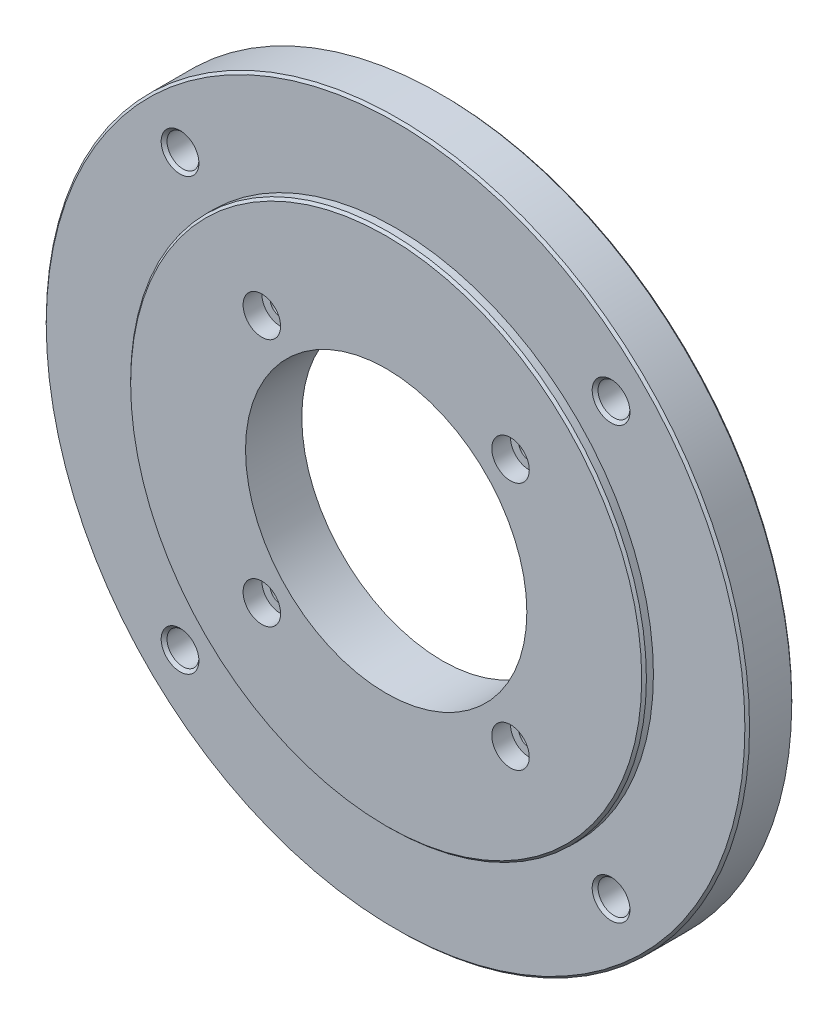
SolidWorks part; units mm, degrees
ref_plane "Front Plane" through (0, 0, 0) normal (0, 0, 1) x (1, 0, 0)
ref_plane "Top Plane" through (0, 0, 0) normal (0, 1, 0) x (1, 0, 0)
ref_plane "Right Plane" through (0, 0, 0) normal (1, 0, 0) x (0, 0, -1)
sketch "Sketch1" plane through (0, 0, 0) normal (0, 0, 1) x (1, 0, 0)
  circle A0 centre (0, 0) radius 75
  dimension "D1" = 150
extrude "Boss-Extrude1" add sketch "Sketch1" along normal blind 10
sketch "Sketch2" plane through (0, 0, 10) normal (0, 0, 1) x (1, 0, 0)
  circle A0 centre (0, 0) radius 55
  dimension "D1" = 110
extrude "Boss-Extrude2" add sketch "Sketch2" along normal blind 2
sketch "Sketch3" plane through (0, 0, 10) normal (0, 0, 1) x (1, 0, 0)
  line L1 (-45.9619, 45.9619) -> (45.9619, 45.9619) construction
  line L2 (-45.9619, 45.9619) -> (-45.9619, -45.9619) construction
  line L3 (-45.9619, -45.9619) -> (45.9619, -45.9619) construction
  line L4 (45.9619, 45.9619) -> (45.9619, -45.9619) construction
  line L5 (-45.9619, 45.9619) -> (45.9619, -45.9619) construction
  line L6 (-45.9619, -45.9619) -> (45.9619, 45.9619) construction
  point P0 (0, 0)
  dimension "D1" = 130
  dimension "D2" = 45
hole_wizard "M8x1.25 Tapped Hole1" positions "3DSketch1" profile "Sketch4" tap size "M8x1.25" standard "ANSI Metric" end condition up to next
sketch3d "3DSketch1"
  point P0 (-45.9619, 45.9619, 10)
  point P3 (45.9619, 45.9619, 10)
  point P6 (-45.9619, -45.9619, 10)
  point P9 (45.9619, -45.9619, 10)
sketch "Sketch4" plane through (-45.9619, 45.9619, 10) normal (1, 0, 0) x (0, -1, 0)
  line L0 (0, 0) -> (0, 10)
  line L1 (0, 10) -> (3.4, 10)
  line L2 (3.4, 10) -> (3.4, 0.625)
  line L3 (3.4, 0.625) -> (4.025, 0)
  line L5 (4.025, 0) -> (0, 0)
  line L6 (-3.4, 0.625) -> (-4.025, 0) construction
  line L11 (0, -6.35) -> (0, 107.95) construction
  dimension "Thru Tap Drill Dia." = 6.8
  dimension "Thru Tap Drill Depth" = 10
  dimension "Near C'Sink Dia." = 8.05
  dimension "Near C'Sink Angle" = 90
cosmetic thread "Hole Thread5" parameters "D2"=8
cosmetic thread "Hole Thread6" parameters "D2"=8
cosmetic thread "Hole Thread7" parameters "D2"=8
cosmetic thread "Hole Thread8" parameters "D2"=8
chamfer "Chamfer1" distance 0.5 angle 45 3 edges at (75, 0, 0) (75, 0, 10) (55, 0, 12)
sketch "Sketch5" plane through (0, 0, 0) normal (0, 0, -1) x (-1, 0, 0)
  circle A0 centre (0, 0) radius 30
  dimension "D1" = 60
extrude "Cut-Extrude1" cut sketch "Sketch5" against normal through all
sketch "Sketch6" plane through (0, 0, 12) normal (0, 0, 1) x (1, 0, 0)
  line L1 (-26.5165, -26.5165) -> (26.5165, -26.5165)
  line L2 (-26.5165, -26.5165) -> (-26.5165, 26.5165)
  line L3 (-26.5165, 26.5165) -> (26.5165, 26.5165)
  line L4 (26.5165, -26.5165) -> (26.5165, 26.5165)
  line L5 (-26.5165, -26.5165) -> (26.5165, 26.5165) construction
  line L6 (-26.5165, 26.5165) -> (26.5165, -26.5165) construction
  point P0 (0, 0)
  dimension "D1" = 75
  dimension "D2" = 45
hole_wizard "CBORE for M4 SHCS1" positions "3DSketch2" profile "Sketch8" counterbore size "M4" standard "ANSI Metric" end condition up to next
sketch3d "3DSketch2"
  point P0 (-26.5165, 26.5165, 12)
  point P3 (26.5165, 26.5165, 12)
  point P6 (-26.5165, -26.5165, 12)
  point P9 (26.5165, -26.5165, 12)
sketch "Sketch8" plane through (-26.5165, 26.5165, 12) normal (1, 0, 0) x (0, -1, 0)
  line L0 (0, 0) -> (0, 12)
  line L1 (0, 12) -> (2.25, 12)
  line L3 (2.25, 12) -> (2.25, 4)
  line L4 (2.25, 4) -> (4, 4)
  line L5 (4, 4) -> (4, 0)
  line L7 (4, 0) -> (0, 0)
  line L11 (0, -6.35) -> (0, 107.95) construction
  dimension "Thru Hole Dia." = 4.5
  dimension "Thru Hole Depth" = 12
  dimension "C'Bore Dia." = 8
  dimension "C'Bore Depth" = 4
